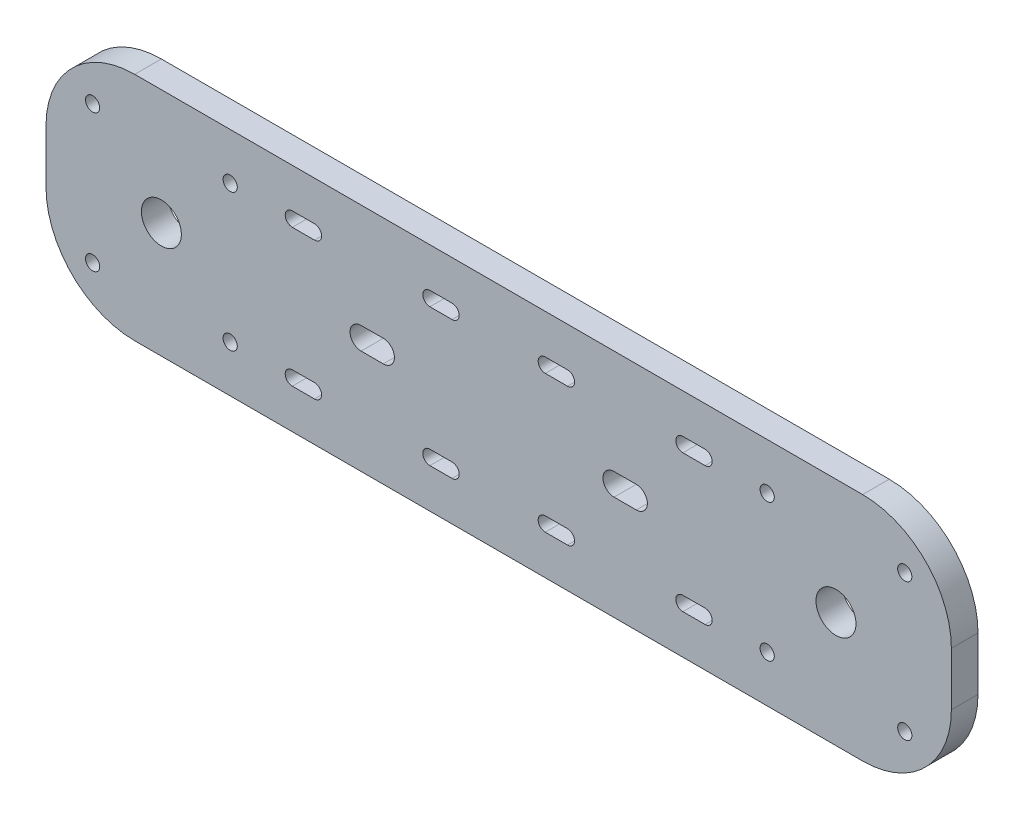
SolidWorks part; units mm, degrees
ref_plane "前视基准面" through (0, 0, 0) normal (0, 0, 1) x (1, 0, 0)
ref_plane "上视基准面" through (0, 0, 0) normal (0, 1, 0) x (1, 0, 0)
ref_plane "右视基准面" through (0, 0, 0) normal (1, 0, 0) x (0, 0, -1)
sketch "草图1" plane through (0, 0, 0) normal (0, 0, 1) x (1, 0, 0)
  line L1 (-102, 26) -> (102, 26)
  line L2 (-102, 26) -> (-102, -26)
  line L3 (-102, -26) -> (102, -26)
  line L4 (102, 26) -> (102, -26)
  line L5 (-102, 26) -> (102, -26) construction
  line L6 (-102, -26) -> (102, 26) construction
  line L7 (-97, 21) -> (-55, 21)
  line L8 (-97, 21) -> (-97, -21)
  line L9 (-97, -21) -> (-55, -21)
  line L10 (-55, 21) -> (-55, -21)
  line L11 (-97, 21) -> (-55, -21) construction
  line L12 (-97, -21) -> (-55, 21) construction
  line L13 (-52, 21) -> (-10, 21)
  line L14 (-52, 21) -> (-52, -21)
  line L15 (-52, -21) -> (-10, -21)
  line L16 (-10, 21) -> (-10, -21)
  line L17 (-52, 21) -> (-10, -21) construction
  line L18 (-52, -21) -> (-10, 21) construction
  line L19 (-47, 21) -> (-5, 21)
  line L20 (-47, 21) -> (-47, -21)
  line L21 (-47, -21) -> (-5, -21)
  line L22 (-5, 21) -> (-5, -21)
  line L23 (-47, 21) -> (-5, -21) construction
  line L24 (-47, -21) -> (-5, 21) construction
  line L25 (55, 21) -> (97, 21)
  line L26 (55, 21) -> (55, -21)
  line L27 (55, -21) -> (97, -21)
  line L28 (97, 21) -> (97, -21)
  line L29 (55, 21) -> (97, -21) construction
  line L30 (55, -21) -> (97, 21) construction
  line L31 (10, 21) -> (52, 21)
  line L32 (10, 21) -> (10, -21)
  line L33 (10, -21) -> (52, -21)
  line L34 (52, 21) -> (52, -21)
  line L35 (10, 21) -> (52, -21) construction
  line L36 (10, -21) -> (52, 21) construction
  line L37 (5, 21) -> (47, 21)
  line L38 (5, 21) -> (5, -21)
  line L39 (5, -21) -> (47, -21)
  line L40 (47, 21) -> (47, -21)
  line L41 (5, 21) -> (47, -21) construction
  line L42 (5, -21) -> (47, 21) construction
  point P0 (0, 0)
  point P6 (-76, 0)
  point P11 (-31, 0)
  point P16 (-26, 0)
  point P21 (76, 0)
  point P26 (31, 0)
  point P31 (26, 0)
  dimension "D1" = 45
  dimension "D2" = 50
  dimension "D3" = 45
  dimension "D4" = 50
  dimension "D5" = 42
  dimension "D6" = 10
  dimension "D7" = 5
  dimension "D8" = 5
  dimension "D9" = 5
extrude "凸台-拉伸1" add sketch "草图1" along normal blind 6 contours L1 L4 L3 L2
sketch "草图2" plane through (0, 0, 6) normal (0, 0, 1) x (1, 0, 0)
  line L0 (-97, 21) -> (-55, -21)
  line L1 (-55, 21) -> (-97, -21)
  line L2 (-110.2628, 15.5) -> (-79.2628, 15.5) construction
  line L3 (55, 21) -> (97, -21) construction
  line L4 (-10, 21) -> (-52, 21)
  line L5 (-10, -21) -> (-10, 21)
  line L6 (-52, -21) -> (-10, -21)
  line L7 (-52, 21) -> (-52, -21)
  line L8 (-10, 21) -> (-52, 21)
  line L9 (-10, -21) -> (-10, 21)
  line L10 (-52, -21) -> (-10, -21)
  line L11 (-52, 21) -> (-52, -21)
  line L12 (-55, 21) -> (-97, 21)
  line L13 (-55, -21) -> (-55, 21)
  line L14 (-97, -21) -> (-55, -21)
  line L15 (-97, 21) -> (-97, -21)
  line L16 (-55, 21) -> (-97, 21)
  line L17 (-55, -21) -> (-55, 21)
  line L18 (-97, -21) -> (-55, -21)
  line L19 (-97, 21) -> (-97, -21)
  line L20 (102, 26) -> (-102, 26)
  line L21 (102, -26) -> (102, 26)
  line L22 (-102, -26) -> (102, -26)
  line L23 (-102, 26) -> (-102, -26)
  line L24 (102, 26) -> (-102, 26)
  line L25 (102, -26) -> (102, 26)
  line L26 (-102, -26) -> (102, -26)
  line L27 (-102, 26) -> (-102, -26)
  line L28 (52, 21) -> (10, 21)
  line L29 (52, -21) -> (52, 21)
  line L30 (10, -21) -> (52, -21)
  line L31 (10, 21) -> (10, -21)
  line L32 (52, 21) -> (10, 21)
  line L33 (52, -21) -> (52, 21)
  line L34 (10, -21) -> (52, -21)
  line L35 (10, 21) -> (10, -21)
  line L36 (97, 21) -> (55, 21)
  line L37 (97, -21) -> (97, 21)
  line L38 (55, -21) -> (97, -21)
  line L39 (55, 21) -> (55, -21)
  line L40 (97, 21) -> (55, 21)
  line L41 (97, -21) -> (97, 21)
  line L42 (55, -21) -> (97, -21)
  line L43 (55, 21) -> (55, -21)
  line L44 (-5, 21) -> (-47, 21)
  line L45 (-5, -21) -> (-5, 21)
  line L46 (-47, -21) -> (-5, -21)
  line L47 (-47, 21) -> (-47, -21)
  line L48 (-5, 21) -> (-47, 21)
  line L49 (-5, -21) -> (-5, 21)
  line L50 (-47, -21) -> (-5, -21)
  line L51 (-47, 21) -> (-47, -21)
  line L52 (47, 21) -> (5, 21)
  line L53 (47, -21) -> (47, 21)
  line L54 (5, -21) -> (47, -21)
  line L55 (5, 21) -> (5, -21)
  line L56 (47, 21) -> (5, 21)
  line L57 (47, -21) -> (47, 21)
  line L58 (5, -21) -> (47, -21)
  line L59 (5, 21) -> (5, -21)
  line L60 (97, 21) -> (55, -21) construction
  line L61 (-102.75, -15.5) -> (-71.0911, -15.5) construction
  line L62 (-52, 21) -> (-10, -21) construction
  line L65 (-10, 21) -> (-52, -21) construction
  line L68 (-47, 21) -> (-5, -21) construction
  line L69 (-5, 21) -> (-47, -21) construction
  line L70 (5, 21) -> (47, -21) construction
  line L71 (47, 21) -> (5, -21) construction
  line L72 (52, 21) -> (10, -21)
  line L73 (10, 21) -> (52, -21) construction
  line L74 (-46.5, 15.5) -> (-41.5, 15.5) construction
  line L75 (-46.5, 17.1) -> (-41.5, 17.1)
  line L76 (-46.5, 13.9) -> (-41.5, 13.9)
  line L77 (-15.5, 15.5) -> (-10.5, 15.5) construction
  line L78 (-15.5, 17.1) -> (-10.5, 17.1)
  line L79 (-15.5, 13.9) -> (-10.5, 13.9)
  line L80 (-46.5, -15.5) -> (-41.5, -15.5) construction
  line L81 (-46.5, -13.9) -> (-41.5, -13.9)
  line L82 (-46.5, -17.1) -> (-41.5, -17.1)
  line L83 (-15.5, -15.5) -> (-10.5, -15.5) construction
  line L84 (-15.5, -13.9) -> (-10.5, -13.9)
  line L85 (-15.5, -17.1) -> (-10.5, -17.1)
  line L86 (10.5, 15.5) -> (15.5, 15.5) construction
  line L87 (10.5, 17.1) -> (15.5, 17.1)
  line L88 (10.5, 13.9) -> (15.5, 13.9)
  line L89 (41.5, 15.5) -> (46.5, 15.5) construction
  line L90 (41.5, 17.1) -> (46.5, 17.1)
  line L91 (41.5, 13.9) -> (46.5, 13.9)
  line L92 (10.5, -15.5) -> (15.5, -15.5) construction
  line L93 (10.5, -13.9) -> (15.5, -13.9)
  line L94 (10.5, -17.1) -> (15.5, -17.1)
  line L95 (41.5, -15.5) -> (46.5, -15.5) construction
  line L96 (41.5, -13.9) -> (46.5, -13.9)
  line L97 (41.5, -17.1) -> (46.5, -17.1)
  line L98 (-31, 0) -> (-26, 0) construction
  line L99 (-31, 2.5) -> (-26, 2.5)
  line L100 (-31, -2.5) -> (-26, -2.5)
  line L101 (26, 0) -> (31, 0) construction
  line L102 (26, 2.5) -> (31, 2.5)
  line L103 (26, -2.5) -> (31, -2.5)
  circle A0 centre (-91.5, 15.5) radius 1.6
  circle A1 centre (-60.5, 15.5) radius 1.6
  circle A2 centre (-91.5, -15.5) radius 1.6
  circle A3 centre (-60.5, -15.5) radius 1.6
  circle A4 centre (60.5, 15.5) radius 1.6
  circle A5 centre (91.5, 15.5) radius 1.6
  circle A6 centre (91.5, -15.5) radius 1.6
  circle A7 centre (60.5, -15.5) radius 1.6
  circle A8 centre (-76, 0) radius 4.5
  circle A9 centre (76, 0) radius 4.5
  arc A14 (-46.5, 17.1) -> (-46.5, 13.9) centre (-46.5, 15.5) ccw
  arc A15 (-41.5, 13.9) -> (-41.5, 17.1) centre (-41.5, 15.5) ccw
  arc A16 (-15.5, 17.1) -> (-15.5, 13.9) centre (-15.5, 15.5) ccw
  arc A17 (-10.5, 13.9) -> (-10.5, 17.1) centre (-10.5, 15.5) ccw
  arc A18 (-46.5, -13.9) -> (-46.5, -17.1) centre (-46.5, -15.5) ccw
  arc A19 (-41.5, -17.1) -> (-41.5, -13.9) centre (-41.5, -15.5) ccw
  arc A20 (-15.5, -13.9) -> (-15.5, -17.1) centre (-15.5, -15.5) ccw
  arc A21 (-10.5, -17.1) -> (-10.5, -13.9) centre (-10.5, -15.5) ccw
  arc A22 (10.5, 17.1) -> (10.5, 13.9) centre (10.5, 15.5) ccw
  arc A23 (15.5, 13.9) -> (15.5, 17.1) centre (15.5, 15.5) ccw
  arc A24 (41.5, 17.1) -> (41.5, 13.9) centre (41.5, 15.5) ccw
  arc A25 (46.5, 13.9) -> (46.5, 17.1) centre (46.5, 15.5) ccw
  arc A26 (10.5, -13.9) -> (10.5, -17.1) centre (10.5, -15.5) ccw
  arc A27 (15.5, -17.1) -> (15.5, -13.9) centre (15.5, -15.5) ccw
  arc A28 (41.5, -13.9) -> (41.5, -17.1) centre (41.5, -15.5) ccw
  arc A29 (46.5, -17.1) -> (46.5, -13.9) centre (46.5, -15.5) ccw
  arc A30 (-31, 2.5) -> (-31, -2.5) centre (-31, 0) ccw
  arc A31 (-26, -2.5) -> (-26, 2.5) centre (-26, 0) ccw
  arc A32 (26, 2.5) -> (26, -2.5) centre (26, 0) ccw
  arc A33 (31, -2.5) -> (31, 2.5) centre (31, 0) ccw
  point P54 (-44, 15.5)
  point P59 (-13, 15.5)
  point P68 (-44, -15.5)
  point P73 (-13, -15.5)
  point P80 (13, 15.5)
  point P87 (44, 15.5)
  point P94 (13, -15.5)
  point P101 (44, -15.5)
  point P108 (-28.5, 0)
  point P115 (28.5, 0)
  dimension "D8" = 31
  dimension "D10" = 9
  dimension "D11" = 3.2
  dimension "D12" = 5
  dimension "D9" = 3.2
  dimension "D1" = 0
  dimension "D2" = 0
  dimension "D3" = 0
  dimension "D4" = 0
  dimension "D5" = 0
  dimension "D6" = 0
  dimension "D7" = 0
extrude "切除-拉伸1" cut sketch "草图2" against normal up to next contours A0 | A1 | A2 | A3 | A4 | A5 | A6 | A7 | L76 A15 L75 A14 | L78 A17 L79 A16 | L88 A23 L87 A22 | L91 A25 L90 A24 | L97 A29 L96 A28 | L94 A27 L93 A26 | L82 A19 L81 A18 | L85 A21 L84 A20 | L100 A30 L99 A31 | L103 A33 L102 A32 | A8 | A9
fillet "圆角3" radius 20 4 edges at (102, -26, 3) (102, 26, 3) (-102, -26, 3) (-102, 26, 3)
